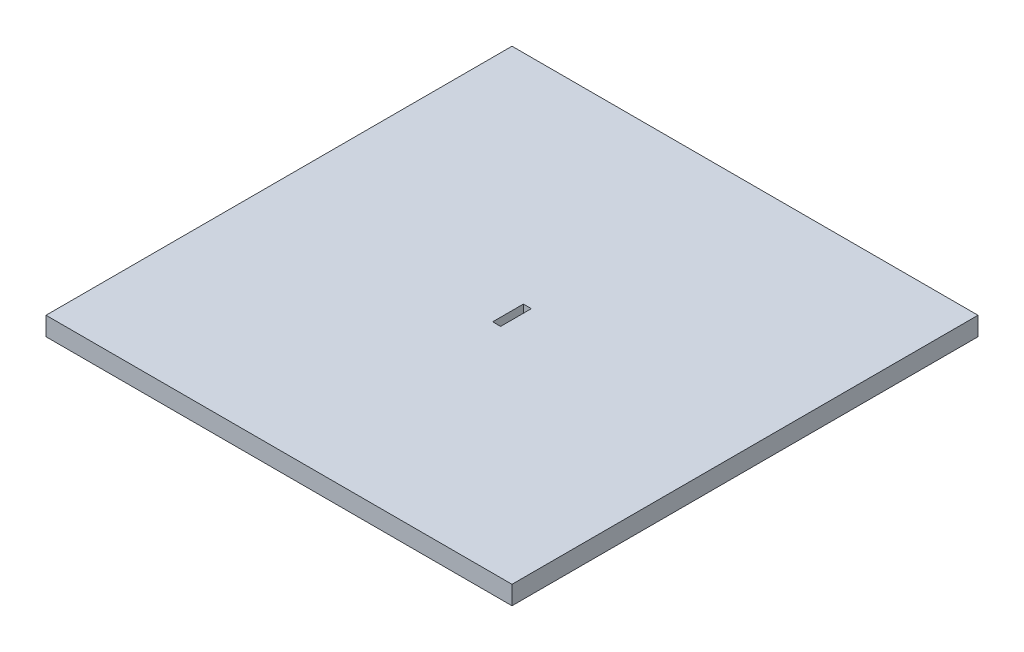
SolidWorks part; units mm, degrees
ref_plane "Front Plane" through (0, 0, 0) normal (0, 0, 1) x (1, 0, 0)
ref_plane "Top Plane" through (0, 0, 0) normal (0, 1, 0) x (1, 0, 0)
ref_plane "Right Plane" through (0, 0, 0) normal (1, 0, 0) x (0, 0, -1)
sketch "Sketch2" plane through (0, 0, 0) normal (0, 1, 0) x (1, 0, 0)
  line L1 (-50, -50) -> (50, -50)
  line L2 (-50, -50) -> (-50, 50)
  line L3 (-50, 50) -> (50, 50)
  line L4 (50, -50) -> (50, 50)
  line L5 (-50, -50) -> (50, 50) construction
  line L6 (-50, 50) -> (50, -50) construction
  point P0 (0, 0)
extrude "Boss-Extrude1" add sketch "Sketch2" along normal blind 4
sketch "Sketch3" plane through (0, 4, 0) normal (0, 1, 0) x (1, 0, 0)
  line L1 (0.855, -3.3) -> (-0.855, -3.3)
  line L2 (0.855, -3.3) -> (0.855, 3.3)
  line L3 (0.855, 3.3) -> (-0.855, 3.3)
  line L4 (-0.855, -3.3) -> (-0.855, 3.3)
  line L5 (0.855, -3.3) -> (-0.855, 3.3) construction
  line L6 (0.855, 3.3) -> (-0.855, -3.3) construction
  point P0 (0, 0)
  point P5 (0, 0)
extrude "Cut-Extrude1" cut sketch "Sketch3" against normal blind 4
